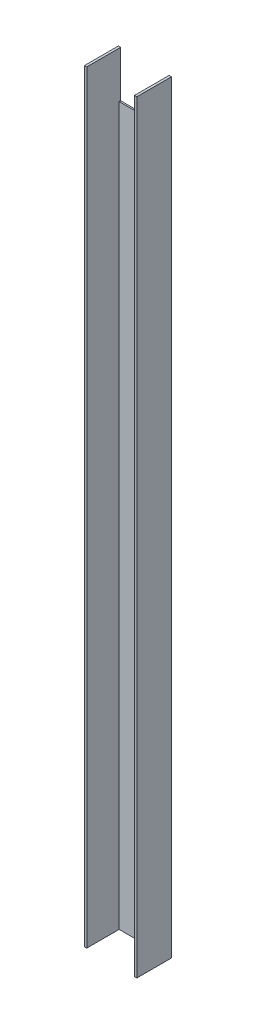
SolidWorks part; units mm, degrees
ref_plane "Front Plane" through (0, 0, 0) normal (0, 0, 1) x (1, 0, 0)
ref_plane "Top Plane" through (0, 0, 0) normal (0, 1, 0) x (1, 0, 0)
ref_plane "Right Plane" through (0, 0, 0) normal (1, 0, 0) x (0, 0, -1)
sketch "Sketch2" plane through (0, 0, 0) normal (0, 1, 0) x (1, 0, 0)
  line L0 (-11.362, -7.2343) -> (-11.362, 7.41)
  line L5 (-11.362, -7.2343) -> (11.638, 7.41) construction
  line L6 (-11.362, 7.41) -> (11.638, -7.59) construction
  line L7 (11.638, 7.41) -> (11.638, -7.59)
  line L8 (-11.362, 7.41) -> (11.638, 7.41)
  line L9 (11.638, -7.59) -> (10.626, -7.59)
  line L10 (10.626, -7.59) -> (10.626, 6.7657)
  line L11 (10.626, 6.7657) -> (-10.374, 6.7657)
  line L12 (-10.374, 6.7657) -> (-10.374, -7.2343)
  line L13 (-10.374, -7.2343) -> (-11.362, -7.2343)
  point P0 (0, 0)
  dimension "D1" = 15
  dimension "D2" = 23
  dimension "D3" = 14
  dimension "D4" = 21
extrude "Boss-Extrude2" add sketch "Sketch2" along normal blind 330
sketch "Sketch3" plane through (0, 330, 0) normal (0, 1, 0) x (1, 0, 0)
  line L0 (-10.374, 6.7657) -> (-10.374, 7.41)
  line L1 (11.638, 7.41) -> (-11.362, 7.41) construction
  line L2 (-10.374, 7.41) -> (10.626, 7.41)
  line L3 (10.626, 7.41) -> (10.626, 6.7657)
  line L4 (10.626, 6.7657) -> (-10.374, 6.7657)
  dimension "D1" = 21
extrude "Cut-Extrude1" cut sketch "Sketch3" against normal blind 20
